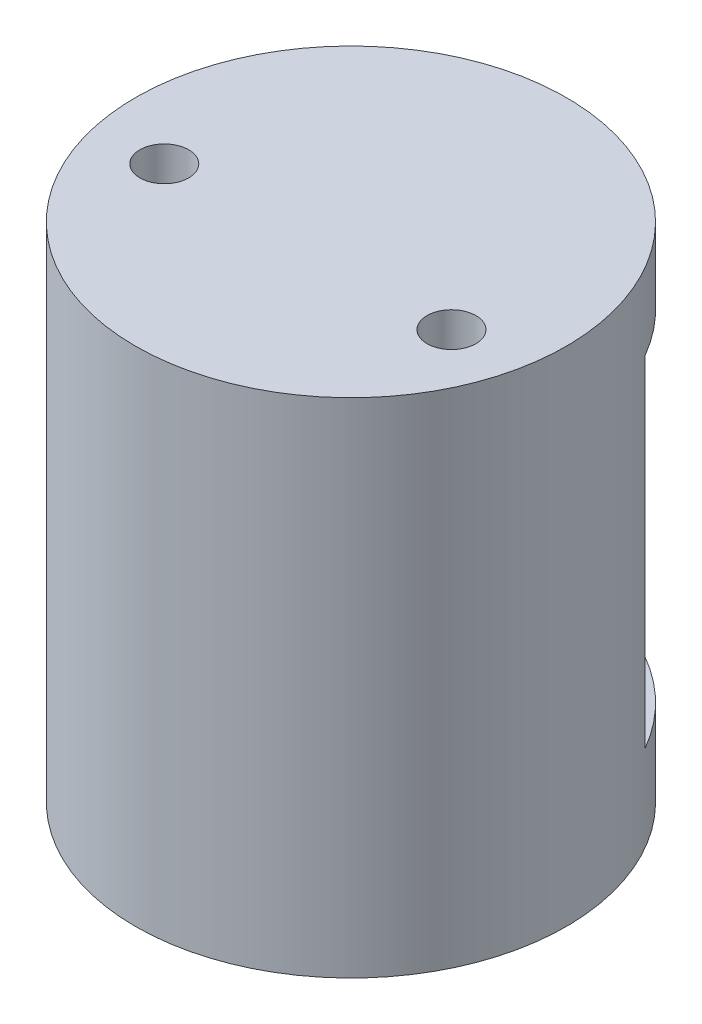
SolidWorks part; units mm, degrees
ref_plane "Front" through (0, 0, 0) normal (0, 0, 1) x (1, 0, 0)
ref_plane "Top" through (0, 0, 0) normal (0, 1, 0) x (1, 0, 0)
ref_plane "Right" through (0, 0, 0) normal (1, 0, 0) x (0, 0, -1)
sketch "Sketch1" plane through (0, 0, 0) normal (0, 1, 0) x (1, 0, 0)
  circle A0 centre (0, 0) radius 15
  dimension "D1" = 30
extrude "Boss-Extrude1" add sketch "Sketch1" along normal blind 35
sketch "Sketch5" plane through (0, 0, 0) normal (1, 0, 0) x (0, 0, -1)
  line L0 (-6, 30.7) -> (-6, 5)
  line L1 (-6, 30.7) -> (0.5, 30.7)
  line L2 (0.5, 30.7) -> (0.5, 29.7)
  line L3 (0.5, 29.7) -> (16, 29.7)
  line L4 (16, 29.7) -> (16, 6)
  line L5 (16, 6) -> (0.5, 6)
  line L6 (0.5, 6) -> (0.5, 5)
  line L7 (0.5, 5) -> (-6, 5)
  line L8 (0, 50) -> (0, -50) construction
  line L9 (-15, 0) -> (15, 0) construction
  dimension "D1" = 25.7
  dimension "D2" = 5
  dimension "D3" = 6.5
  dimension "D4" = 16
  dimension "D5" = 1
  dimension "D6" = 1
  dimension "D7" = 6
extrude "Cut-Extrude4" cut sketch "Sketch5" against normal blind 16 and the other way blind 13
sketch "Sketch6" plane through (0, 0, 0) normal (0, -1, 0) x (1, 0, 0)
  line L0 (-9.6979, 8.2) -> (9.6979, 8.2)
  arc A0 (-9.6979, 8.2) -> (9.6979, 8.2) centre (0, 0) ccw
  dimension "D1" = 25.4
  dimension "D2" = 8.2
extrude "Cut-Extrude5" cut sketch "Sketch6" against normal blind 1.5
sketch "Sketch7" plane through (0, 1.5, 0) normal (0, -1, 0) x (1, 0, 0)
  circle A0 centre (0, -6) radius 2.1
  dimension "D1" = 4.2
  dimension "D2" = 6
extrude "Cut-Extrude6" cut sketch "Sketch7" against normal blind 2.2
ref_plane "Optical axis" through (0, 17.7, 0) normal (0, 1, 0) x (1, 0, 0)
sketch "Sketch8" plane through (0, 35, 0) normal (0, 1, 0) x (1, 0, 0)
  circle A0 centre (-10, -3) radius 1.7
  circle A1 centre (10, -3) radius 1.7
  dimension "D4" = 3.4
  dimension "D1" = 10
  dimension "D2" = 20
  dimension "D3" = 3
extrude "Cut-Extrude7" cut sketch "Sketch8" against normal up to next
